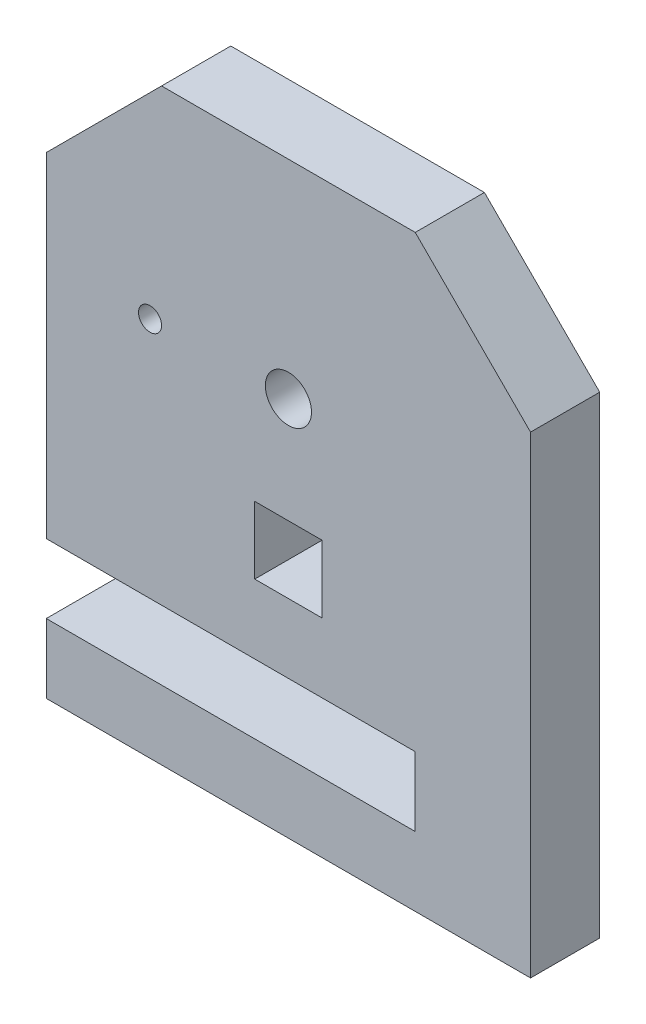
SolidWorks part; units mm, degrees
ref_plane "Front Plane" through (0, 0, 0) normal (0, 0, 1) x (1, 0, 0)
ref_plane "Top Plane" through (0, 0, 0) normal (0, 1, 0) x (1, 0, 0)
ref_plane "Right Plane" through (0, 0, 0) normal (1, 0, 0) x (0, 0, -1)
sketch "Sketch1" plane through (0, 0, 0) normal (0, 0, 1) x (1, 0, 0)
  line L0 (8.5483, 11.7097) -> (13.5483, 6.7097)
  line L1 (-7.4517, 11.7097) -> (13.5483, 11.7097)
  line L2 (-7.4517, 11.7097) -> (-7.4517, -7.7903)
  line L3 (-7.4517, -13.7903) -> (13.5483, -13.7903)
  line L4 (13.5483, 11.7097) -> (13.5483, -13.7903)
  line L5 (3.0483, 11.7097) -> (3.0483, 6.905) construction
  line L6 (-2.4517, 11.7097) -> (-7.4517, 6.7097)
  line L7 (-7.4517, -10.7903) -> (8.5483, -10.7903)
  line L8 (1.5883, -1.8703) -> (4.5083, -1.8703)
  line L9 (1.5883, -1.8703) -> (1.5883, -4.7903)
  line L10 (1.5883, -4.7903) -> (4.5083, -4.7903)
  line L11 (4.5083, -1.8703) -> (4.5083, -4.7903)
  line L12 (8.5483, -10.7903) -> (8.5483, -7.7903)
  line L13 (8.5483, -7.7903) -> (-7.4517, -7.7903)
  line L14 (-7.4517, -10.7903) -> (-7.4517, -13.7903)
  circle A0 centre (3.0483, 2.7097) radius 1
  circle A1 centre (-2.9517, 2.7097) radius 0.5
  point P16 (3.0483, -1.8703)
  dimension "D5" = 2
  dimension "D6" = 16.5
  dimension "D11" = 1
  dimension "D12" = 6
  dimension "D1" = 25.5
  dimension "D2" = 21
  dimension "D3" = 5
  dimension "D4" = 5
  dimension "D7" = 2.92
  dimension "D8" = 2.92
  dimension "D9" = 9
  dimension "D10" = 10.5
  dimension "D13" = 3
  dimension "D14" = 16
  dimension "D15" = 3
  dimension "D16" = 5
extrude "Boss-Extrude1" add sketch "Sketch1" along normal blind 3
